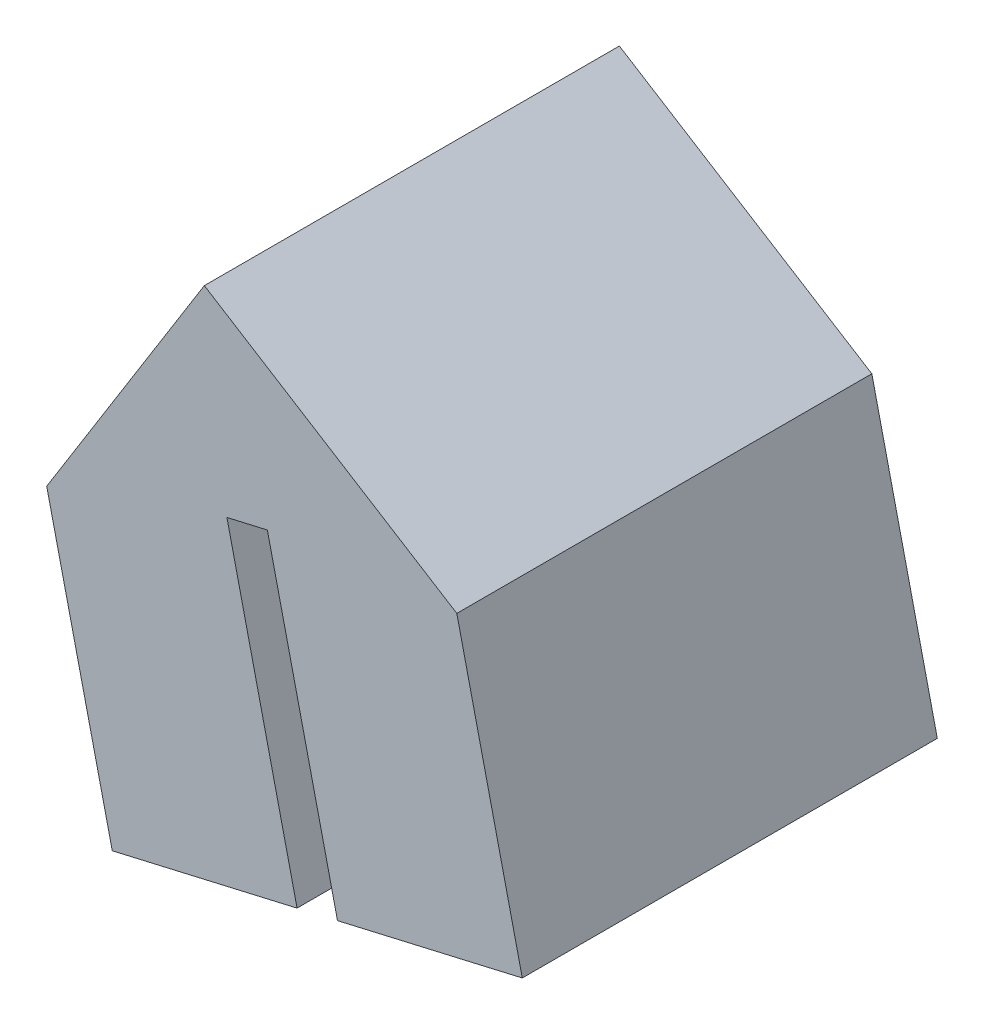
SolidWorks part; units mm, degrees
ref_plane "Plan de face" through (0, 0, 0) normal (0, 0, 1) x (1, 0, 0)
ref_plane "Plan de dessus" through (0, 0, 0) normal (0, 1, 0) x (1, 0, 0)
ref_plane "Plan de droite" through (0, 0, 0) normal (1, 0, 0) x (0, 0, -1)
sketch "Esquisse1" plane through (0, 0, 0) normal (0, 0, 1) x (1, 0, 0)
  line L0 (0, 0) -> (10.5912, 16.9654)
  line L1 (10.5912, 16.9654) -> (27.5567, 6.3742)
  line L3 (0, 0) -> (2.2578, -9.7418)
  line L13 (2.2578, -9.7418) -> (29.8103, -3.3686)
  line L14 (29.8103, -3.3686) -> (27.5567, 6.3742)
  dimension "D1" = 20
  dimension "D2" = 20
  dimension "D3" = 28.28
  dimension "D4" = 10
  dimension "D5" = 10
extrude "Boss.-Extru.1" add sketch "Esquisse1" along normal blind 20
sketch "Esquisse3" plane through (0, 0, 20) normal (0, 0, 1) x (1, 0, 0)
  line L0 (15.0598, -6.7805) -> (17.0083, -6.3298)
  line L2 (17.0083, -6.3298) -> (13.6279, 8.2843)
  line L3 (13.6279, 8.2843) -> (11.6793, 7.8336)
  line L4 (11.6793, 7.8336) -> (15.0598, -6.7805)
  line L5 (2.2578, -9.7418) -> (29.8103, -3.3686) construction
  point P2 (0, 0)
  point P4 (13.2429, 3.0632)
  point P7 (0, 0)
  dimension "D1" = 2
  dimension "D2" = 13.14
  dimension "D3" = 15
extrude "Enlèv. mat.-Extru.1" cut sketch "Esquisse3" against normal blind 20
sketch "Esquisse4" plane through (0, 0, 20) normal (0, 0, 1) x (1, 0, 0)
  line L0 (6.1549, -8.8403) -> (2.9944, 4.7965)
  line L1 (2.2578, -9.7418) -> (15.0598, -6.7805) construction
  line L2 (10.5912, 16.9654) -> (0, 0) construction
  line L3 (2.9944, 4.7965) -> (-5.3724, 2.556)
  line L4 (-5.3724, 2.556) -> (0.8831, -10.6722)
  line L5 (0.8831, -10.6722) -> (6.3948, -10.3003)
  line L6 (6.3948, -10.3003) -> (6.1549, -8.8403)
  line L7 (0, 0) -> (2.2578, -9.7418) construction
  line L8 (25.9132, -4.27) -> (22.7581, 9.3699)
  line L9 (17.0083, -6.3298) -> (29.8103, -3.3686) construction
  line L10 (27.5567, 6.3742) -> (10.5912, 16.9654) construction
  line L11 (22.7581, 9.3699) -> (37.6933, 8.1138)
  line L12 (37.6933, 8.1138) -> (39.4642, -8.8992)
  line L13 (39.4642, -8.8992) -> (30.3894, -4.2884)
  line L14 (30.3894, -4.2884) -> (25.9132, -4.27)
  line L15 (29.8103, -3.3686) -> (27.5567, 6.3742) construction
  dimension "D1" = 4
  dimension "D2" = 4
extrude "Enlèv. mat.-Extru.2" cut sketch "Esquisse4" against normal blind 20
